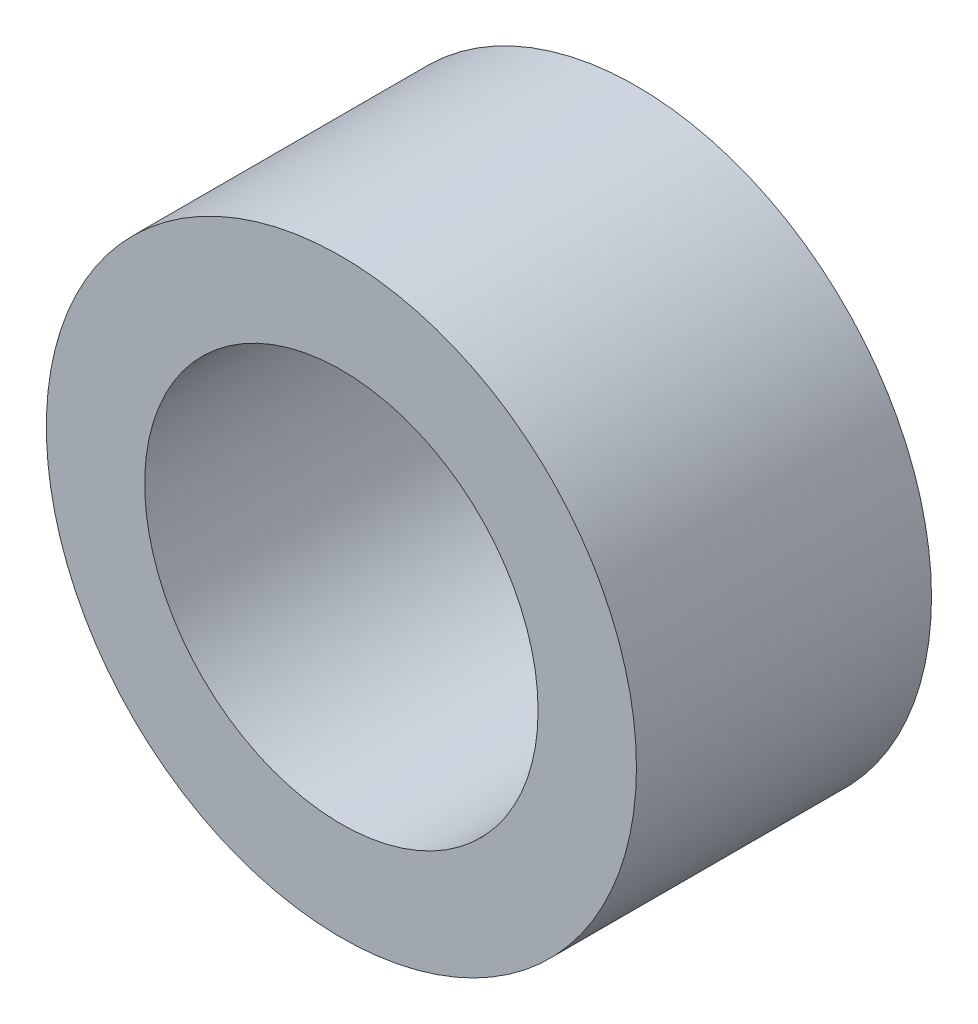
SolidWorks part; units mm, degrees
ref_plane "Front" through (0, 0, 0) normal (0, 0, 1) x (1, 0, 0)
ref_plane "Top" through (0, 0, 0) normal (0, 1, 0) x (1, 0, 0)
ref_plane "Right" through (0, 0, 0) normal (1, 0, 0) x (0, 0, -1)
sketch "草图1" plane through (0, 0, 0) normal (0, 0, 1) x (1, 0, 0)
  circle A0 centre (0, 0) radius 4
  circle A1 centre (0, 0) radius 6
  dimension "D1" = 12
  dimension "D2" = 8
extrude "凸台-拉伸1" add sketch "草图1" along normal blind 6
